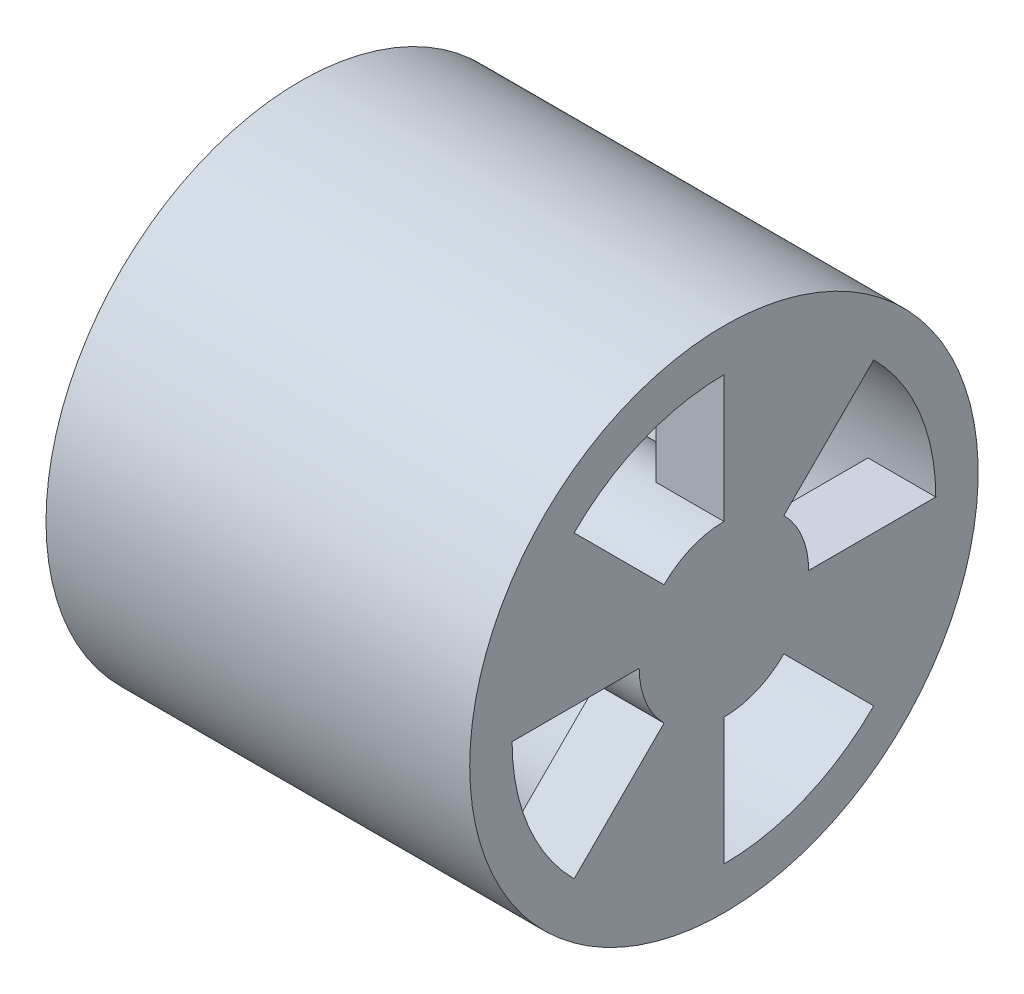
SolidWorks part; units mm, degrees
ref_plane "Front Plane" through (0, 0, 0) normal (0, 0, 1) x (1, 0, 0)
ref_plane "Top Plane" through (0, 0, 0) normal (0, 1, 0) x (1, 0, 0)
ref_plane "Right Plane" through (0, 0, 0) normal (1, 0, 0) x (0, 0, -1)
sketch "Sketch1" plane through (0, 0, 0) normal (0, 0, 1) x (1, 0, 0)
  line L1 (0, 0) -> (25, 0) construction
  line L2 (0, 0) -> (0, 15) construction
  line L3 (0, 15) -> (25, 15) construction
  line L4 (25, 0) -> (25, 15) construction
  line L5 (0, 15) -> (25, 15)
  line L6 (0, 15) -> (0, 12.5)
  line L7 (0, 12.5) -> (25, 12.5)
  line L8 (25, 15) -> (25, 12.5)
  dimension "D1" = 25
  dimension "D2" = 15
  dimension "D3" = 2.5
revolve "Revolve1" add sketch "Sketch1" angle 360 about L1
sketch "Sketch2" plane through (0, 0, 0) normal (0, 0, 1) x (1, 0, 0)
  line L0 (0, 0) -> (25, 0) construction
  line L1 (25, -15) -> (25, 15) construction
  line L2 (8, 0) -> (8, 12.5)
  line L3 (25, 12.5) -> (0, 12.5) construction
  line L4 (8, 12.5) -> (25, 12.5)
  line L5 (25, 12.5) -> (25, 0)
  line L6 (25, 0) -> (8, 0)
  line L7 (0, 15) -> (0, -15) construction
  dimension "D1" = 8
revolve "Revolve2" add sketch "Sketch2" angle 360 about L0
sketch "Sketch3" plane through (8, 0, 0) normal (-1, 0, 0) x (0, 0, 1)
  line L0 (0.8292, 1.25) -> (0.8292, -1.25)
  arc A0 (0.8292, 1.25) -> (0.8292, -1.25) centre (0, 0) ccw
  dimension "D1" = 3
  dimension "D2" = 2.5
extrude "Cut-Extrude1" cut sketch "Sketch3" against normal blind 10
sketch "Sketch4" plane through (8, 0, 0) normal (-1, 0, 0) x (0, 0, 1)
  circle A0 centre (0, 0) radius 5
  circle A1 centre (0, 0) radius 12.5
  dimension "D1" = 25
  dimension "D2" = 10
extrude "Cut-Extrude2" cut sketch "Sketch4" against normal blind 13
sketch "Sketch5" plane through (21, 0, 0) normal (-1, 0, 0) x (0, 0, 1)
  line L0 (-12.5, 0) -> (12.5, 0)
  line L1 (0, 12.5) -> (0, -12.5)
  line L2 (-8.8388, 8.8388) -> (8.8388, -8.8388)
  line L3 (-8.8388, -8.8388) -> (8.8388, 8.8388)
  circle A0 centre (0, 0) radius 12.5
  circle M5 centre (0, 0) radius 5
  circle M6 centre (0, 0) radius 12.5
  dimension "D1" = 45
  dimension "D2" = 45
extrude "Cut-Extrude3" cut sketch "Sketch5" against normal through all contours L2 L0 M6 M5 | L3 L1 M5 M6 | L2 L0 M5 M6 | L3 L1 M6 M5
